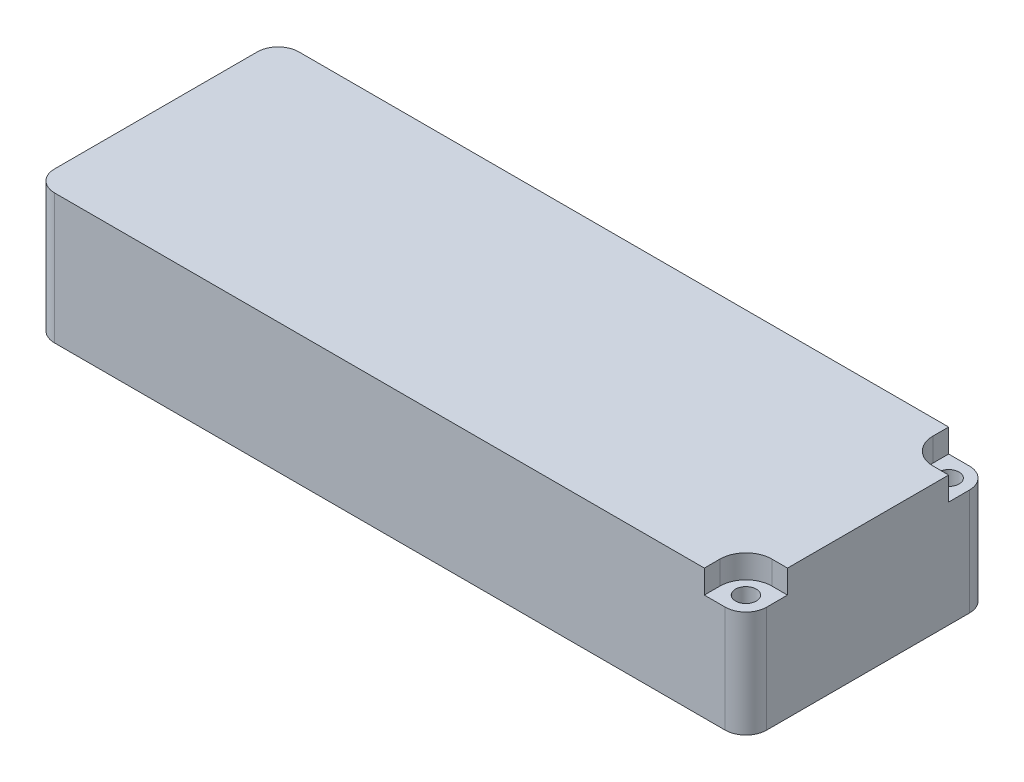
SolidWorks part; units mm, degrees
material "Thornel Mat VMA"
ref_plane "Front Plane" through (0, 0, 0) normal (0, 0, 1) x (1, 0, 0)
ref_plane "Top Plane" through (0, 0, 0) normal (0, 1, 0) x (1, 0, 0)
ref_plane "Right Plane" through (0, 0, 0) normal (1, 0, 0) x (0, 0, -1)
sketch "Sketch1" plane through (0, 0, 0) normal (0, 1, 0) x (1, 0, 0)
  line L1 (-68.5, -23.5) -> (68.5, -23.5)
  line L2 (-68.5, -23.5) -> (-68.5, 23.5)
  line L3 (-68.5, 23.5) -> (68.5, 23.5)
  line L4 (68.5, -23.5) -> (68.5, 23.5)
  line L5 (-68.5, -23.5) -> (68.5, 23.5) construction
  line L6 (-68.5, 23.5) -> (68.5, -23.5) construction
  point P0 (0, 0)
  dimension "D1" = 47
  dimension "D2" = 137
extrude "Boss-Extrude1" add sketch "Sketch1" along normal blind 25 contours L3 L4 L1 L2
fillet "Fillet1" radius 4 4 edges at (-68.5, 12.5, -23.5) (68.5, 12.5, -23.5) (68.5, 12.5, 23.5) (-68.5, 12.5, 23.5)
sketch "Sketch2" plane through (0, 25, 0) normal (0, 1, 0) x (1, 0, 0)
  line L0 (60.5, 23.5) -> (60.5, 15.5)
  line L2 (-64.5, 23.5) -> (64.5, 23.5) construction
  line L3 (60.5, 15.5) -> (68.5, 15.5)
  line L4 (68.5, -19.5) -> (68.5, 19.5) construction
  line L5 (68.5, 15.5) -> (68.5, 23.5)
  line L6 (68.5, 23.5) -> (60.5, 23.5)
  line L7 (0, 0) -> (97.334, 0) construction
  line L8 (68.5, -23.5) -> (60.5, -23.5)
  line L9 (68.5, -15.5) -> (68.5, -23.5)
  line L10 (60.5, -15.5) -> (68.5, -15.5)
  line L11 (60.5, -23.5) -> (60.5, -15.5)
  dimension "D1" = 8
  dimension "D2" = 8
extrude "Cut-Extrude1" cut sketch "Sketch2" against normal blind 4.5
fillet "Fillet2" radius 5 2 edges at (60.5, 22.75, -15.5) (60.5, 22.75, 15.5)
sketch "Sketch3" plane through (0, 20.5, 0) normal (0, 1, 0) x (1, 0, 0)
  line L0 (0, 0) -> (76.532, 0) construction
  circle A1 centre (64.5, 19.5) radius 2
  circle A2 centre (64.5, -19.5) radius 2
  dimension "D1" = 4
extrude "Cut-Extrude2" cut sketch "Sketch3" against normal blind 10
